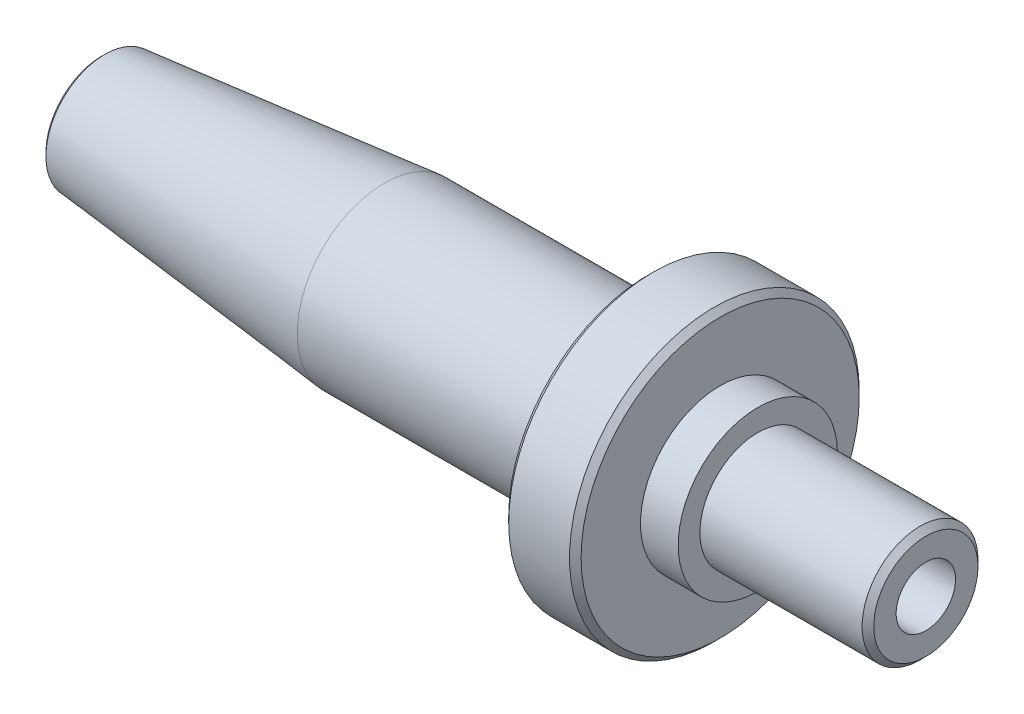
SolidWorks part; units mm, degrees
ref_plane "Face" through (0, 0, 0) normal (0, 0, 1) x (1, 0, 0)
ref_plane "Dessus" through (0, 0, 0) normal (0, 1, 0) x (1, 0, 0)
ref_plane "Droite" through (0, 0, 0) normal (1, 0, 0) x (0, 0, -1)
sketch "Esquisse1" plane through (0, 0, 0) normal (0, 0, 1) x (1, 0, 0)
  line L0 (14.225, 0) -> (-14.225, 0) construction
  line L1 (-14.225, 0) -> (-14.225, 2.025)
  line L2 (-14.225, 2.025) -> (-4.475, 3)
  line L3 (-4.475, 3) -> (3.625, 3)
  line L4 (3.625, 3) -> (3.625, 3.5)
  line L5 (3.625, 3.5) -> (4.625, 3.5)
  line L6 (4.625, 3.5) -> (4.625, 5)
  line L7 (4.625, 5) -> (7.125, 5)
  line L8 (7.125, 5) -> (7.125, 2.75)
  line L9 (8.425, 2) -> (14.225, 2)
  line L10 (14.225, 2) -> (14.225, 0)
  line L11 (14.225, 0) -> (-14.225, 0)
  line L12 (7.125, 2.75) -> (8.425, 2.75)
  line L13 (8.425, 2.75) -> (8.425, 2)
  dimension "D2" = 5.8
  dimension "D3" = 2.5
  dimension "D4" = 1
  dimension "D5" = 8.1
  dimension "D6" = 4
  dimension "D7" = 10
  dimension "D8" = 7
  dimension "D9" = 6
  dimension "D10" = 9.75
  dimension "D11" = 0.975
  dimension "D12" = 9.75
  dimension "D13" = 3.8
  dimension "D14" = 2.75
revolve "Révolution1" add sketch "Esquisse1" angle 360 about L0
chamfer "Chanfrein1" distance 0.1 angle 45 1 edges at (-14.225, 0, -2.025)
chamfer "Chanfrein2" distance 0.2 angle 45 1 edges at (3.625, 0, -3.5)
chamfer "Chanfrein3" distance 0.2 angle 45 3 edges at (14.225, 0, -2) (7.125, 0, -5) (4.625, 0, -5)
hole_wizard "Trou taraudé M31" positions "Esquisse3" profile "Esquisse2" tap size "M3" standard "ISO"
sketch "Esquisse3" plane through (-14.225, 0, 0) normal (-1, 0, 0) x (0, 0, 1)
  point P0 (0, 0)
sketch "Esquisse2" plane through (-14.225, 0, 0) normal (0, 1, 0) x (0, 0, 1)
  line L0 (0, 0) -> (0, 9.2511)
  line L1 (0, 9.2511) -> (1.25, 8.5)
  line L2 (1.25, 8.5) -> (1.25, 0)
  line L5 (1.25, 0) -> (0, 0)
  line L10 (0, 9.2511) -> (-1.25, 8.5) construction
  line L11 (0, -6.35) -> (0, 107.95) construction
  dimension "Diamètre du trou pour taraudage" = 2.5
  dimension "Profondeur du trou pour taraudage" = 8.5
  dimension "Angle de pointe" = 118
cosmetic thread "Filetage de perçage1" parameters "D1"=6, "D2"=3
hole_wizard "Trou taraudé M2.51" positions "Esquisse5" profile "Esquisse4" tap size "M2.5" standard "ISO"
sketch "Esquisse5" plane through (14.225, 0, 0) normal (1, 0, 0) x (0, 0, -1)
  point P0 (0, 0)
sketch "Esquisse4" plane through (14.225, 0, 0) normal (0, 1, 0) x (0, 0, -1)
  line L0 (0, 0) -> (0, 8.8659)
  line L1 (0, 8.8659) -> (1.025, 8.25)
  line L2 (1.025, 8.25) -> (1.025, 0)
  line L5 (1.025, 0) -> (0, 0)
  line L10 (0, 8.8659) -> (-1.025, 8.25) construction
  line L11 (0, -6.35) -> (0, 107.95) construction
  dimension "Diamètre du trou pour taraudage" = 2.05
  dimension "Profondeur du trou pour taraudage" = 8.25
  dimension "Angle de pointe" = 118
cosmetic thread "Filetage de perçage2" parameters "D1"=6, "D2"=2.5
equation "\"D11@Esquisse1\"=\"D10@Esquisse1\"/10"
